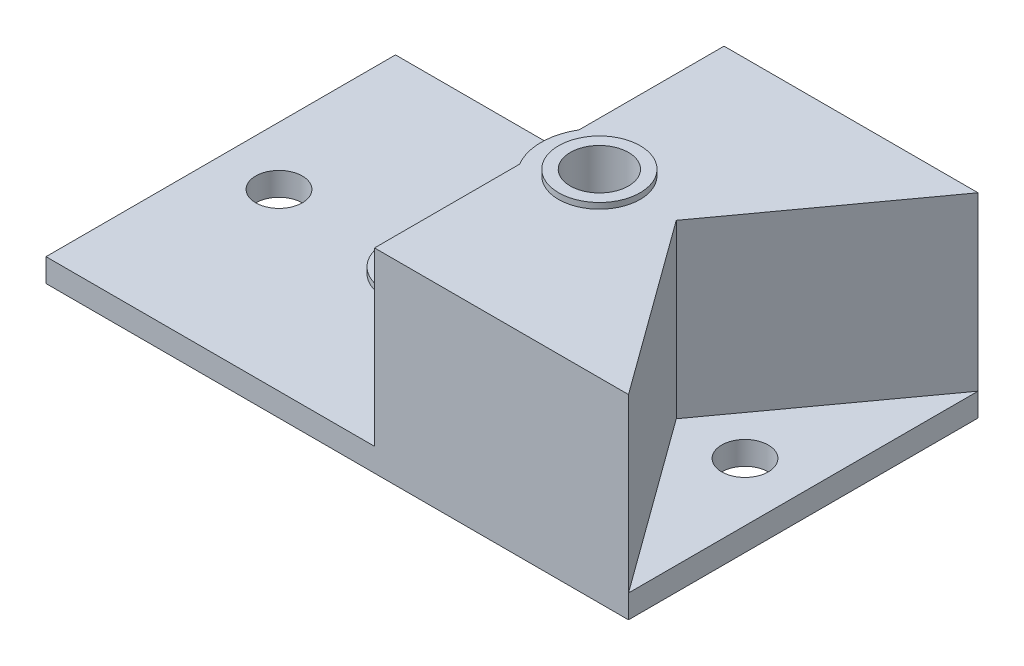
SolidWorks part; units mm, degrees
ref_plane "Front Plane" through (0, 0, 0) normal (0, 0, 1) x (1, 0, 0)
ref_plane "Top Plane" through (0, 0, 0) normal (0, 1, 0) x (1, 0, 0)
ref_plane "Right Plane" through (0, 0, 0) normal (1, 0, 0) x (0, 0, -1)
sketch "Sketch1" plane through (0, 0, 0) normal (0, 1, 0) x (1, 0, 0)
  line L1 (0, 0) -> (50, 0)
  line L2 (0, 0) -> (0, 30)
  line L3 (0, 30) -> (50, 30)
  line L4 (50, 0) -> (50, 30)
  circle A0 centre (5, 15) radius 2
  circle A1 centre (45, 15) radius 2
  circle A2 centre (17.5, 15) radius 2.5
  circle A3 centre (32.5, 15) radius 2.5
  dimension "D1" = 4
  dimension "D2" = 4
  dimension "D9" = 5
  dimension "D10" = 5
  dimension "D3" = 30
  dimension "D4" = 15
  dimension "D5" = 15
  dimension "D6" = 5
  dimension "D7" = 5
  dimension "D8" = 50
  dimension "D11" = 15
  dimension "D12" = 15
  dimension "D13" = 15
  dimension "D14" = 17.5
extrude "Boss-Extrude1" add sketch "Sketch1" along normal blind 2
sketch "Sketch2" plane through (0, 2, 0) normal (0, 1, 0) x (1, 0, 0)
  circle A0 centre (32.5, 15) radius 2.5
  circle A1 centre (32.5, 15) radius 5
  dimension "D2" = 10
extrude "Boss-Extrude2" add sketch "Sketch2" along normal blind 14.75
sketch "Sketch3" plane through (0, 2, 0) normal (0, 1, 0) x (1, 0, 0)
  circle A0 centre (17.5, 15) radius 3.5
  circle A1 centre (17.5, 15) radius 2.5
  dimension "D1" = 7
extrude "Boss-Extrude3" add sketch "Sketch3" along normal blind 0.5
sketch "Sketch4" plane through (0, 16.75, 0) normal (0, 1, 0) x (1, 0, 0)
  circle A0 centre (32.5, 15) radius 2.5
  circle A1 centre (32.5, 15) radius 3.5
  dimension "D1" = 7
extrude "Boss-Extrude4" add sketch "Sketch4" along normal blind 0.5
sketch "Sketch5" plane through (0, 2, 0) normal (0, 1, 0) x (1, 0, 0)
  line L0 (28.2008, 30) -> (28.2008, 17.5528)
  line L1 (50, 30) -> (0, 30) construction
  line L3 (28.2008, 12.4472) -> (28.2008, 0)
  line L4 (0, 0) -> (50, 0) construction
  line L5 (28.2008, 0) -> (50, 0)
  line L6 (50, 0) -> (39.1004, 15)
  line L7 (39.1004, 15) -> (50, 30)
  line L8 (50, 30) -> (28.2008, 30)
  circle A0 centre (32.5, 15) radius 5 construction
  circle A1 centre (32.5, 15) radius 5 construction
  arc A2 (28.2008, 17.5528) -> (28.2008, 12.4472) centre (32.5, 15) ccw
  circle A3 centre (32.5, 15) radius 5
  circle M1 centre (32.5, 15) radius 5
  line M4 (0, 0) -> (50, 0)
  line M6 (50, 30) -> (0, 30)
extrude "Boss-Extrude5" add sketch "Sketch5" along normal blind 14.75 contours L6 L7 L0 L3 M6 M1 M4
